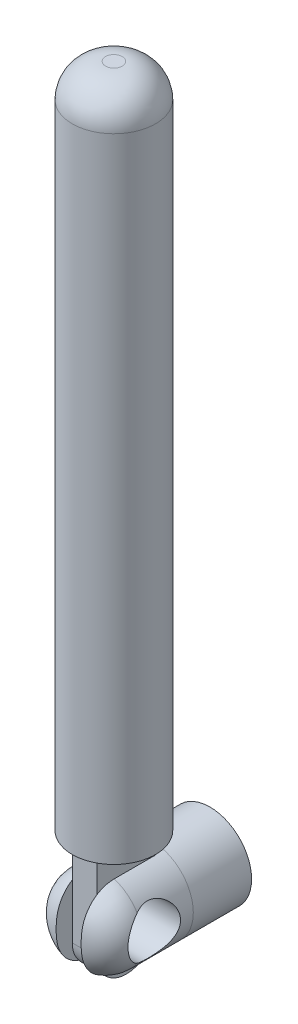
SolidWorks part; units mm, degrees
ref_plane "Спереди" through (0, 0, 0) normal (0, 0, 1) x (1, 0, 0)
ref_plane "Сверху" through (0, 0, 0) normal (0, 1, 0) x (1, 0, 0)
ref_plane "Справа" through (0, 0, 0) normal (1, 0, 0) x (0, 0, -1)
sketch "Эскиз1" plane through (0, 0, 0) normal (0, 0, 1) x (1, 0, 0)
  circle A0 centre (0, 0) radius 5
extrude "Вытянуть1" add sketch "Эскиз1" along normal blind 7
sketch "Эскиз3" plane through (0, 0, 7) normal (0, 0, 1) x (1, 0, 0)
  circle A0 centre (0, 0) radius 5
extrude "Вытянуть3" add sketch "Эскиз3" along normal blind 10 separate body
fillet "Скругление1" radius 4 1 edges at (5, 0, 17)
sketch "Эскиз4" plane through (0, 0, 17) normal (0, 0, 1) x (1, 0, 0)
  line L1 (-1.5, 5.6718) -> (1.5, 5.6718)
  line L2 (-1.5, 5.6718) -> (-1.5, -5.6718)
  line L3 (-1.5, -5.6718) -> (1.5, -5.6718)
  line L4 (1.5, 5.6718) -> (1.5, -5.6718)
  line L5 (-1.5, 5.6718) -> (1.5, -5.6718) construction
  line L6 (-1.5, -5.6718) -> (1.5, 5.6718) construction
  point P0 (0, 0)
extrude "Вытянуть5" cut sketch "Эскиз4" against normal blind 9
sketch "Эскиз5" plane through (-1.5, 0, 0) normal (1, 0, 0) x (0, 0, -1)
  circle A0 centre (-11.5358, 0) radius 3
extrude "Вытянуть6" cut sketch "Эскиз5" against normal mid plane 37
sketch "Эскиз6" plane through (-1.5, 0, 0) normal (1, 0, 0) x (0, 0, -1)
  line L0 (-15.0358, -2.3687) -> (-15.0358, 8.3181)
  line L1 (-15.0358, 8.3181) -> (-8.0358, 8.3181)
  line L2 (-8.0358, 8.3181) -> (-8.0358, -2.3577)
  arc A0 (-8.0358, -2.3577) -> (-15.0358, -2.3687) centre (-11.5358, -2.3632) cw
extrude "Вытянуть7" add sketch "Эскиз6" along normal blind 3
sketch "Эскиз7" plane through (0, 8.3181, 0) normal (0, 1, 0) x (-1, 0, 0)
  circle A0 centre (0, 11.5358) radius 5
extrude "Вытянуть8" add sketch "Эскиз7" along normal blind 80
fillet "Скругление2" radius 4 1 edges at (-5, 88.3181, 11.5358)
sketch "Эскиз8" plane through (1.5, 0, 0) normal (1, 0, 0) x (0, 0, -1)
  circle A0 centre (-11.5358, 0) radius 3
extrude "Вытянуть9" cut sketch "Эскиз8" against normal through all
